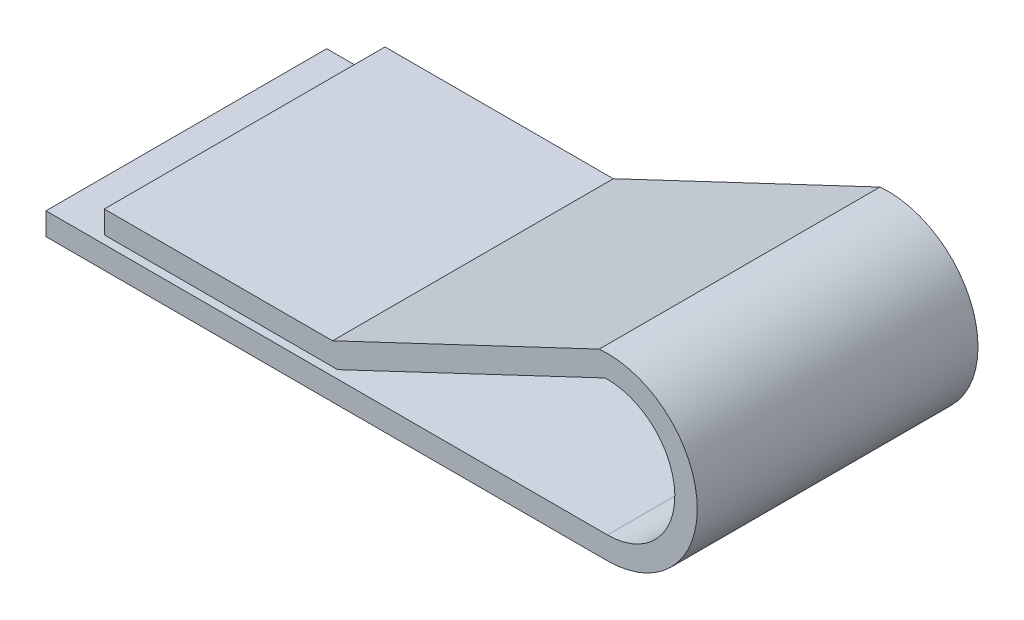
SolidWorks part; units mm, degrees
material "Nylon 101"
ref_plane "Front Plane" through (0, 0, 0) normal (0, 0, 1) x (1, 0, 0)
ref_plane "Top Plane" through (0, 0, 0) normal (0, 1, 0) x (1, 0, 0)
ref_plane "Right Plane" through (0, 0, 0) normal (1, 0, 0) x (0, 0, -1)
sketch "Sketch1" plane through (0, 0, 0) normal (0, 0, 1) x (1, 0, 0)
  line L0 (-40.0773, 0) -> (9.9227, 0)
  line L1 (9.7038, 11.996) -> (-14.1076, 0.7339)
  line L2 (-14.1076, 0.7339) -> (-34.8856, 0.7339)
  line L3 (-40.0773, 0) -> (-40.0773, 28.0534) construction
  arc A0 (9.9227, 0) -> (9.7038, 11.996) centre (9.9227, 6) ccw
  dimension "D1" = 6
  dimension "D2" = 50
extrude "Extrude-Thin1" add sketch "Sketch1" along normal mid plane 25 thin
